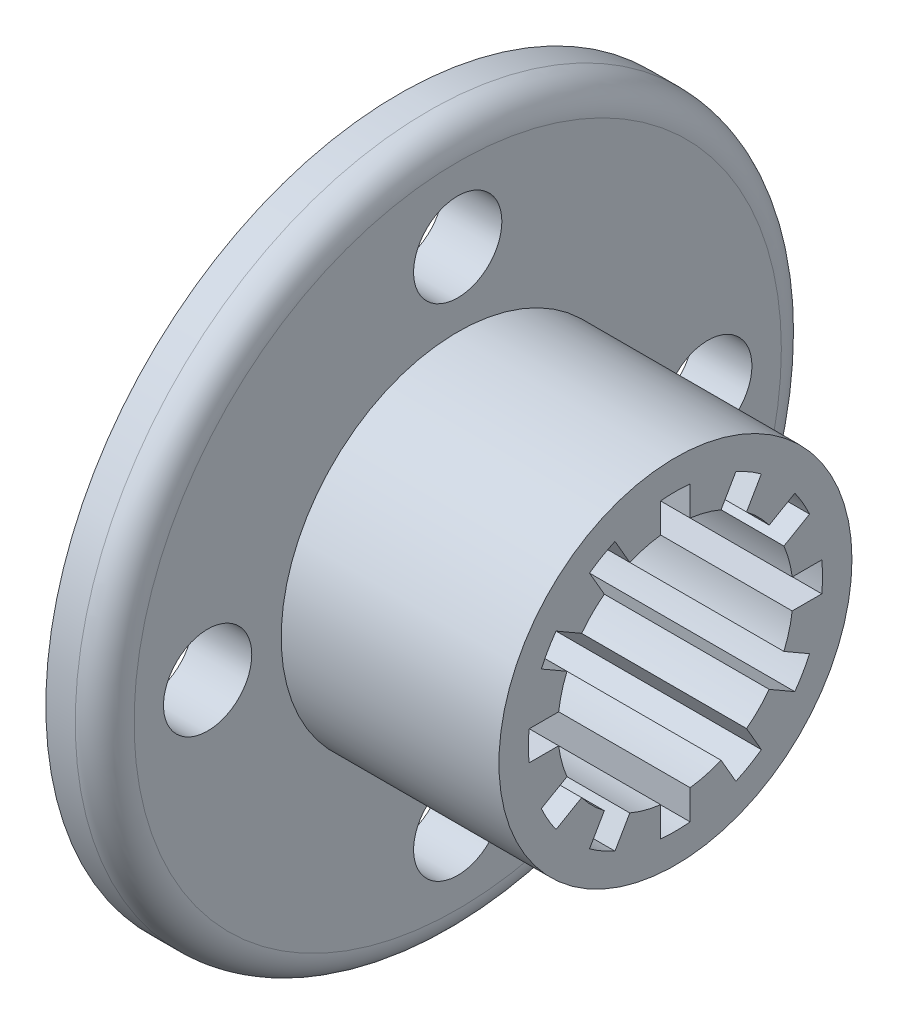
SolidWorks part; units mm, degrees
ref_plane "Front Plane" through (0, 0, 0) normal (0, 0, 1) x (1, 0, 0)
ref_plane "Top Plane" through (0, 0, 0) normal (0, 1, 0) x (1, 0, 0)
ref_plane "Right Plane" through (0, 0, 0) normal (1, 0, 0) x (0, 0, -1)
sketch "Sketch1" plane through (0, 0, 0) normal (1, 0, 0) x (0, 0, -1)
  circle A0 centre (0, 0) radius 6
  dimension "D1" = 12
extrude "Boss-Extrude1" add sketch "Sketch1" along normal blind 1
fillet "Fillet2" radius 0.5 1 edges at (1, 0, -6)
sketch "Sketch3" plane through (1, 0, 0) normal (1, 0, 0) x (0, 0, -1)
  circle A0 centre (0, 0) radius 3
  circle A1 centre (0, 0) radius 2.5
  dimension "D1" = 6
  dimension "D2" = 5
extrude "Boss-Extrude2" add sketch "Sketch3" along normal blind 3.7
sketch "Sketch4" plane through (1, 0, 0) normal (1, 0, 0) x (0, 0, -1)
  circle A0 centre (0, 0) radius 2.5
extrude "Cut-Extrude1" cut sketch "Sketch4" against normal through all
sketch "Sketch5" plane through (1, 0, 0) normal (1, 0, 0) x (0, 0, -1)
  line L0 (-3.8944, 0) -> (4.2655, 0) construction
  line L1 (-2.5377, 0.25) -> (-1.9843, 0.25)
  line L2 (-2.5377, -0.25) -> (-1.9843, -0.25)
  line L3 (-2.0727, 1.4854) -> (-1.5935, 1.2087)
  line L4 (-2.3227, 1.0524) -> (-1.8435, 0.7757)
  line L5 (-1.0524, 2.3227) -> (-0.7757, 1.8435)
  line L6 (-1.4854, 2.0727) -> (-1.2087, 1.5935)
  line L7 (0.25, 2.5377) -> (0.25, 1.9843)
  line L8 (-0.25, 2.5377) -> (-0.25, 1.9843)
  line L9 (1.4854, 2.0727) -> (1.2087, 1.5935)
  line L10 (1.0524, 2.3227) -> (0.7757, 1.8435)
  line L11 (2.3227, 1.0524) -> (1.8435, 0.7757)
  line L12 (2.0727, 1.4854) -> (1.5935, 1.2087)
  line L13 (2.5377, -0.25) -> (1.9843, -0.25)
  line L14 (2.5377, 0.25) -> (1.9843, 0.25)
  line L15 (2.0727, -1.4854) -> (1.5935, -1.2087)
  line L16 (2.3227, -1.0524) -> (1.8435, -0.7757)
  line L17 (1.0524, -2.3227) -> (0.7757, -1.8435)
  line L18 (1.4854, -2.0727) -> (1.2087, -1.5935)
  line L19 (-0.25, -2.5377) -> (-0.25, -1.9843)
  line L20 (0.25, -2.5377) -> (0.25, -1.9843)
  line L21 (-1.4854, -2.0727) -> (-1.2087, -1.5935)
  line L22 (-1.0524, -2.3227) -> (-0.7757, -1.8435)
  line L23 (-2.3227, -1.0524) -> (-1.8435, -0.7757)
  line L24 (-2.0727, -1.4854) -> (-1.5935, -1.2087)
  arc A0 (-1.2087, 1.5935) -> (-1.5935, 1.2087) centre (0, 0) ccw
  arc A1 (-1.4854, 2.0727) -> (-2.0727, 1.4854) centre (0, 0) ccw
  arc A2 (-0.25, 2.5377) -> (-1.0524, 2.3227) centre (0, 0) ccw
  arc A3 (-0.25, 1.9843) -> (-0.7757, 1.8435) centre (0, 0) ccw
  arc A4 (1.0524, 2.3227) -> (0.25, 2.5377) centre (0, 0) ccw
  arc A5 (0.7757, 1.8435) -> (0.25, 1.9843) centre (0, 0) ccw
  arc A6 (2.0727, 1.4854) -> (1.4854, 2.0727) centre (0, 0) ccw
  arc A7 (1.5935, 1.2087) -> (1.2087, 1.5935) centre (0, 0) ccw
  arc A8 (2.5377, 0.25) -> (2.3227, 1.0524) centre (0, 0) ccw
  arc A9 (1.9843, 0.25) -> (1.8435, 0.7757) centre (0, 0) ccw
  arc A10 (2.3227, -1.0524) -> (2.5377, -0.25) centre (0, 0) ccw
  arc A11 (1.8435, -0.7757) -> (1.9843, -0.25) centre (0, 0) ccw
  arc A12 (1.2087, -1.5935) -> (1.5935, -1.2087) centre (0, 0) ccw
  arc A13 (1.4854, -2.0727) -> (2.0727, -1.4854) centre (0, 0) ccw
  arc A14 (0.25, -1.9843) -> (0.7757, -1.8435) centre (0, 0) ccw
  arc A15 (0.25, -2.5377) -> (1.0524, -2.3227) centre (0, 0) ccw
  arc A16 (-0.7757, -1.8435) -> (-0.25, -1.9843) centre (0, 0) ccw
  arc A17 (-1.0524, -2.3227) -> (-0.25, -2.5377) centre (0, 0) ccw
  arc A18 (-1.5935, -1.2087) -> (-1.2087, -1.5935) centre (0, 0) ccw
  arc A19 (-2.0727, -1.4854) -> (-1.4854, -2.0727) centre (0, 0) ccw
  arc A20 (-1.9843, -0.25) -> (-1.8435, -0.7757) centre (0, 0) ccw
  arc A21 (-2.5377, -0.25) -> (-2.3227, -1.0524) centre (0, 0) ccw
  arc A22 (-1.8435, 0.7757) -> (-1.9843, 0.25) centre (0, 0) ccw
  arc A23 (-2.3227, 1.0524) -> (-2.5377, 0.25) centre (0, 0) ccw
  point P57 (0, 0)
  dimension "D1" = 4
  dimension "D2" = 5.1
  dimension "D3" = 0.25
  dimension "D4" = 0.25
  dimension "D5" = 12
extrude "Boss-Extrude3" add sketch "Sketch5" along normal through all
sketch "Sketch6" plane through (1, 0, 0) normal (1, 0, 0) x (0, 0, -1)
  line L0 (-8.6685, 0) -> (8.3905, 0) construction
  circle A4 centre (-4.25, 0) radius 0.75
  circle A5 centre (0, 4.25) radius 0.75
  circle A6 centre (4.25, 0) radius 0.75
  circle A7 centre (0, -4.25) radius 0.75
  point P17 (0, 0)
  dimension "D2" = 1.5
  dimension "D3" = 4
extrude "Cut-Extrude2" cut sketch "Sketch6" against normal through all
